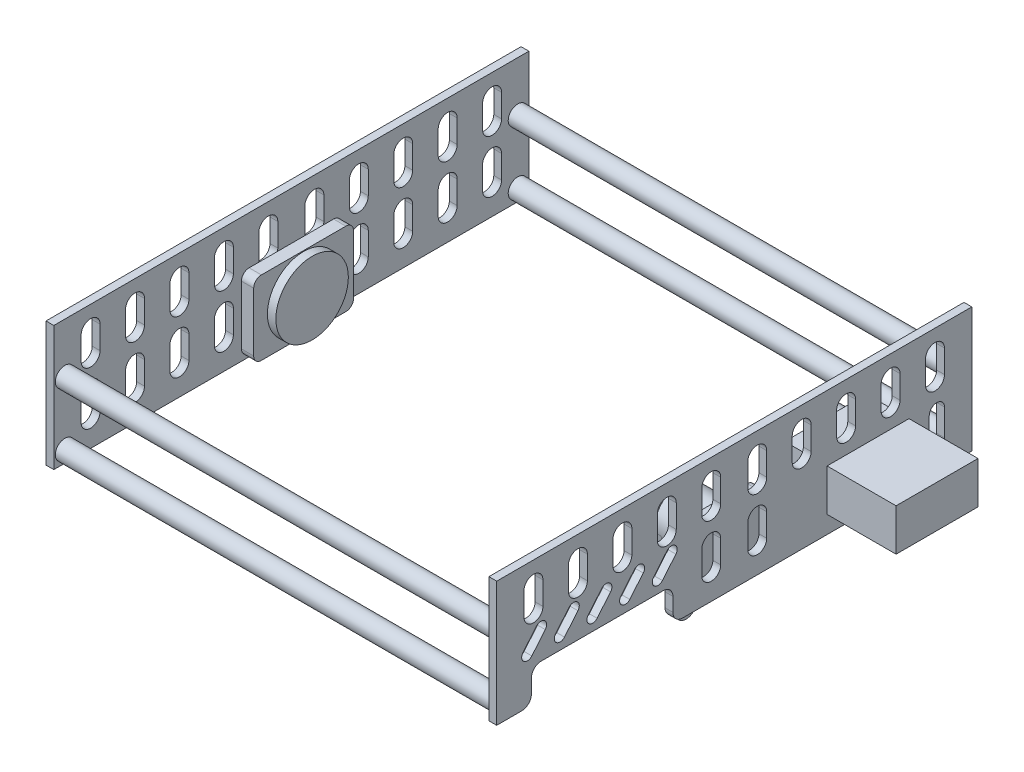
SolidWorks part; units mm, degrees
ref_plane "Front Plane" through (0, 0, 0) normal (0, 0, 1) x (1, 0, 0)
ref_plane "Top Plane" through (0, 0, 0) normal (0, 1, 0) x (1, 0, 0)
ref_plane "Right Plane" through (0, 0, 0) normal (1, 0, 0) x (0, 0, -1)
sketch "Sketch1" plane through (0, 0, 0) normal (1, 0, 0) x (0, 0, -1)
  line L0 (0, 0) -> (0, -16.4338) construction
  line L1 (0, 0) -> (55.8004, 0) construction
  line L2 (0, -16.4338) -> (117.9322, -16.4338) construction
  line L3 (117.9322, -16.4338) -> (117.9322, 0) construction
  line L4 (-2.5019, -18.9357) -> (120.4341, -18.9357) construction
  line L5 (-2.5019, 2.5019) -> (120.4341, 2.5019) construction
  line L6 (-2.5019, 2.5019) -> (-2.5019, -18.9357) construction
  line L7 (120.4341, 2.5019) -> (120.4341, -18.9357) construction
  circle A0 centre (0, 0) radius 2.5019
  circle A1 centre (0, -16.4338) radius 2.5019
  circle A2 centre (117.9322, -16.4338) radius 2.5019
  circle A3 centre (117.9322, 0) radius 2.5019
  dimension "D2" = 5.0038
  dimension "D3" = 21.4376
  dimension "D4" = 122.936
extrude "Boss-Extrude1" add sketch "Sketch1" along normal blind 115.316
ref_plane "Plane1" through (12.7, 0, 0) normal (1, 0, 0) x (0, 0, -1)
sketch "Sketch5" plane through (0, 0, 0) normal (1, 0, 0) x (0, 0, -1)
  line L4 (0, 0) -> (117.9322, -16.4338) construction
  line L5 (58.9661, 12.954) -> (58.9661, -19.558) construction
  line L6 (4.2291, -14.9987) -> (4.2291, 9.7028) construction
  line L8 (6.6941, 1.2458) -> (6.6941, 7.2378) construction
  line L10 (4.2291, 9.7028) -> (113.7031, 9.7028) construction
  line L15 (113.7031, -14.9987) -> (4.2291, -14.9987) construction
  line L20 (117.9322, 0) -> (0, -16.4338) construction
  line L29 (64.9581, 1.2458) -> (64.9581, 7.2378) construction
  line L38 (67.4231, 1.2458) -> (67.4231, 7.2378)
  line L45 (62.4931, 1.2458) -> (62.4931, 7.2378)
  line L52 (64.9581, -12.5337) -> (64.9581, -6.5417) construction
  line L61 (67.4231, -12.5337) -> (67.4231, -6.5417)
  line L70 (62.4931, -12.5337) -> (62.4931, -6.5417)
  line L76 (-2.8829, -19.558) -> (120.8151, -19.558)
  line L77 (-2.8829, -19.558) -> (-2.8829, 12.954)
  line L78 (-2.8829, 12.954) -> (120.8151, 12.954)
  line L79 (120.8151, -19.558) -> (120.8151, 12.954)
  line L80 (76.5281, -12.5337) -> (76.5281, -6.5417) construction
  line L81 (78.9931, -12.5337) -> (78.9931, -6.5417)
  line L82 (4.2291, 1.2458) -> (4.2291, 7.2378)
  line L83 (9.1591, 1.2458) -> (9.1591, 7.2378)
  line L84 (4.2291, 9.7028) -> (9.1591, 9.7028) construction
  line L85 (9.1591, 9.7028) -> (9.1591, -1.2192) construction
  line L86 (9.1591, -1.2192) -> (4.2291, -1.2192) construction
  line L87 (4.2291, -1.2192) -> (4.2291, 9.7028) construction
  line L88 (18.2641, 1.2458) -> (18.2641, 7.2378) construction
  line L89 (15.7991, 1.2458) -> (15.7991, 7.2378)
  line L90 (20.7291, 1.2458) -> (20.7291, 7.2378)
  line L91 (29.8341, 1.2458) -> (29.8341, 7.2378) construction
  line L92 (27.3691, 1.2458) -> (27.3691, 7.2378)
  line L93 (32.2991, 1.2458) -> (32.2991, 7.2378)
  line L94 (41.4041, 1.2458) -> (41.4041, 7.2378) construction
  line L95 (38.9391, 1.2458) -> (38.9391, 7.2378)
  line L96 (43.8691, 1.2458) -> (43.8691, 7.2378)
  line L97 (52.9741, 1.2458) -> (52.9741, 7.2378) construction
  line L98 (50.5091, 1.2458) -> (50.5091, 7.2378)
  line L99 (55.4391, 1.2458) -> (55.4391, 7.2378)
  line L100 (18.2641, -12.5337) -> (18.2641, -6.5417) construction
  line L101 (15.7991, -12.5337) -> (15.7991, -6.5417)
  line L102 (20.7291, -12.5337) -> (20.7291, -6.5417)
  line L103 (29.8341, -12.5337) -> (29.8341, -6.5417) construction
  line L104 (27.3691, -12.5337) -> (27.3691, -6.5417)
  line L105 (32.2991, -12.5337) -> (32.2991, -6.5417)
  line L106 (41.4041, -12.5337) -> (41.4041, -6.5417) construction
  line L107 (38.9391, -12.5337) -> (38.9391, -6.5417)
  line L108 (43.8691, -12.5337) -> (43.8691, -6.5417)
  line L109 (52.9741, -12.5337) -> (52.9741, -6.5417) construction
  line L110 (50.5091, -12.5337) -> (50.5091, -6.5417)
  line L111 (55.4391, -12.5337) -> (55.4391, -6.5417)
  line L112 (6.6941, -12.5337) -> (6.6941, -6.5417) construction
  line L113 (4.2291, -12.5337) -> (4.2291, -6.5417)
  line L114 (9.1591, -12.5337) -> (9.1591, -6.5417)
  line L116 (74.0631, -12.5337) -> (74.0631, -6.5417)
  line L117 (113.7031, 9.7028) -> (113.7031, -14.9987) construction
  line L118 (76.5281, 1.2458) -> (76.5281, 7.2378) construction
  line L119 (78.9931, 1.2458) -> (78.9931, 7.2378)
  line L120 (74.0631, 1.2458) -> (74.0631, 7.2378)
  line L121 (88.0981, 1.2458) -> (88.0981, 7.2378) construction
  line L122 (90.5631, 1.2458) -> (90.5631, 7.2378)
  line L123 (85.6331, 1.2458) -> (85.6331, 7.2378)
  line L124 (88.0981, -12.5337) -> (88.0981, -6.5417) construction
  line L125 (90.5631, -12.5337) -> (90.5631, -6.5417)
  line L126 (85.6331, -12.5337) -> (85.6331, -6.5417)
  line L127 (99.6681, -12.5337) -> (99.6681, -6.5417) construction
  line L128 (102.1331, -12.5337) -> (102.1331, -6.5417)
  line L129 (97.2031, -12.5337) -> (97.2031, -6.5417)
  line L130 (99.6681, 1.2458) -> (99.6681, 7.2378) construction
  line L131 (102.1331, 1.2458) -> (102.1331, 7.2378)
  line L132 (97.2031, 1.2458) -> (97.2031, 7.2378)
  line L133 (111.2381, 1.2458) -> (111.2381, 7.2378) construction
  line L134 (113.7031, 1.2458) -> (113.7031, 7.2378)
  line L135 (108.7731, 1.2458) -> (108.7731, 7.2378)
  line L136 (111.2381, -12.5337) -> (111.2381, -6.5417) construction
  line L137 (113.7031, -12.5337) -> (113.7031, -6.5417)
  line L138 (108.7731, -12.5337) -> (108.7731, -6.5417)
  line L140 (-6.1459, 2.5019) -> (0, 2.5019) construction
  arc A40 (4.2291, 1.2458) -> (9.1591, 1.2458) centre (6.6941, 1.2458) ccw
  arc A41 (9.1591, 7.2378) -> (4.2291, 7.2378) centre (6.6941, 7.2378) ccw
  arc A42 (15.7991, 1.2458) -> (20.7291, 1.2458) centre (18.2641, 1.2458) ccw
  arc A43 (20.7291, 7.2378) -> (15.7991, 7.2378) centre (18.2641, 7.2378) ccw
  arc A44 (27.3691, 1.2458) -> (32.2991, 1.2458) centre (29.8341, 1.2458) ccw
  arc A45 (32.2991, 7.2378) -> (27.3691, 7.2378) centre (29.8341, 7.2378) ccw
  arc A46 (38.9391, 1.2458) -> (43.8691, 1.2458) centre (41.4041, 1.2458) ccw
  arc A47 (43.8691, 7.2378) -> (38.9391, 7.2378) centre (41.4041, 7.2378) ccw
  arc A48 (50.5091, 1.2458) -> (55.4391, 1.2458) centre (52.9741, 1.2458) ccw
  arc A49 (55.4391, 7.2378) -> (50.5091, 7.2378) centre (52.9741, 7.2378) ccw
  arc A50 (15.7991, -12.5337) -> (20.7291, -12.5337) centre (18.2641, -12.5337) ccw
  arc A51 (20.7291, -6.5417) -> (15.7991, -6.5417) centre (18.2641, -6.5417) ccw
  arc A52 (27.3691, -12.5337) -> (32.2991, -12.5337) centre (29.8341, -12.5337) ccw
  arc A53 (32.2991, -6.5417) -> (27.3691, -6.5417) centre (29.8341, -6.5417) ccw
  arc A54 (38.9391, -12.5337) -> (43.8691, -12.5337) centre (41.4041, -12.5337) ccw
  arc A55 (43.8691, -6.5417) -> (38.9391, -6.5417) centre (41.4041, -6.5417) ccw
  arc A56 (50.5091, -12.5337) -> (55.4391, -12.5337) centre (52.9741, -12.5337) ccw
  arc A57 (55.4391, -6.5417) -> (50.5091, -6.5417) centre (52.9741, -6.5417) ccw
  arc A58 (4.2291, -12.5337) -> (9.1591, -12.5337) centre (6.6941, -12.5337) ccw
  arc A59 (9.1591, -6.5417) -> (4.2291, -6.5417) centre (6.6941, -6.5417) ccw
  circle A60 centre (0, 0) radius 2.5019 construction
  circle A61 centre (0, -16.4338) radius 2.5019 construction
  circle A62 centre (117.9322, 0) radius 2.5019 construction
  circle A63 centre (117.9322, -16.4338) radius 2.5019 construction
  arc A64 (67.4231, 1.2458) -> (62.4931, 1.2458) centre (64.9581, 1.2458) cw
  arc A65 (62.4931, 7.2378) -> (67.4231, 7.2378) centre (64.9581, 7.2378) cw
  arc A66 (67.4231, -12.5337) -> (62.4931, -12.5337) centre (64.9581, -12.5337) cw
  arc A67 (62.4931, -6.5417) -> (67.4231, -6.5417) centre (64.9581, -6.5417) cw
  arc A68 (78.9931, -12.5337) -> (74.0631, -12.5337) centre (76.5281, -12.5337) cw
  arc A69 (74.0631, -6.5417) -> (78.9931, -6.5417) centre (76.5281, -6.5417) cw
  arc A70 (78.9931, 1.2458) -> (74.0631, 1.2458) centre (76.5281, 1.2458) cw
  arc A71 (74.0631, 7.2378) -> (78.9931, 7.2378) centre (76.5281, 7.2378) cw
  arc A72 (90.5631, 1.2458) -> (85.6331, 1.2458) centre (88.0981, 1.2458) cw
  arc A73 (85.6331, 7.2378) -> (90.5631, 7.2378) centre (88.0981, 7.2378) cw
  arc A74 (90.5631, -12.5337) -> (85.6331, -12.5337) centre (88.0981, -12.5337) cw
  arc A75 (85.6331, -6.5417) -> (90.5631, -6.5417) centre (88.0981, -6.5417) cw
  arc A76 (102.1331, -12.5337) -> (97.2031, -12.5337) centre (99.6681, -12.5337) cw
  arc A77 (97.2031, -6.5417) -> (102.1331, -6.5417) centre (99.6681, -6.5417) cw
  arc A78 (102.1331, 1.2458) -> (97.2031, 1.2458) centre (99.6681, 1.2458) cw
  arc A79 (97.2031, 7.2378) -> (102.1331, 7.2378) centre (99.6681, 7.2378) cw
  arc A80 (113.7031, 1.2458) -> (108.7731, 1.2458) centre (111.2381, 1.2458) cw
  arc A81 (108.7731, 7.2378) -> (113.7031, 7.2378) centre (111.2381, 7.2378) cw
  arc A82 (113.7031, -12.5337) -> (108.7731, -12.5337) centre (111.2381, -12.5337) cw
  arc A83 (108.7731, -6.5417) -> (113.7031, -6.5417) centre (111.2381, -6.5417) cw
  point P15 (58.9661, -8.2169)
  point P19 (64.9581, 4.2418)
  point P26 (64.9581, -9.5377)
  point P36 (76.5281, -9.5377)
  point P43 (76.5281, 4.2418)
  point P50 (88.0981, 4.2418)
  point P57 (88.0981, -9.5377)
  point P64 (99.6681, -9.5377)
  point P71 (99.6681, 4.2418)
  point P78 (111.2381, 4.2418)
  point P88 (111.2381, -9.5377)
  point P100 (58.9661, -7.9692)
  point P166 (6.6941, 4.2418)
  point P180 (18.2641, 4.2418)
  point P187 (29.8341, 4.2418)
  point P194 (41.4041, 4.2418)
  point P201 (52.9741, 4.2418)
  point P208 (18.2641, -9.5377)
  point P215 (29.8341, -9.5377)
  point P222 (41.4041, -9.5377)
  point P229 (52.9741, -9.5377)
  point P236 (6.6941, -9.5377)
  dimension "D3" = 123.698
  dimension "D2" = 16.5
  dimension "D4" = 10.4521
  dimension "D11" = 32.512
  dimension "D13" = 3.2512
  dimension "D14" = 7.112
  dimension "D15" = 4.93
  dimension "D16" = 10.922
  dimension "D19" = 13.7795
  dimension "D17" = 5
  dimension "D18" = 2
extrude "Boss-Extrude3" add sketch "Sketch5" along normal blind 2.032
ref_plane "Plane2" through (115.316, 0, 0) normal (1, 0, 0) x (0, 0, -1)
sketch "Sketch6" plane through (115.316, 0, 0) normal (1, 0, 0) x (0, 0, -1)
  line L0 (120.8151, 12.954) -> (-2.8829, 12.954) construction
  line L1 (-2.8829, -19.558) -> (3.6195, -19.558)
  line L2 (-2.8829, -19.558) -> (-2.8829, 12.954)
  line L3 (-2.8829, 12.954) -> (120.8151, 12.954)
  line L4 (120.8151, -19.558) -> (120.8151, 12.954)
  line L5 (-2.8829, -19.558) -> (120.8151, 12.954) construction
  line L6 (-2.8829, 12.954) -> (120.8151, -19.558) construction
  line L7 (-2.8829, 12.954) -> (-2.8829, -19.558) construction
  line L8 (6.1595, -17.018) -> (6.1595, -13.4112)
  line L9 (8.6995, -10.8712) -> (40.4495, -10.8712)
  line L10 (42.9895, -13.4112) -> (42.9895, -17.018)
  line L11 (45.5295, -19.558) -> (120.8151, -19.558)
  line L12 (52.9741, -6.5417) -> (52.9741, -12.5337) construction
  line L13 (55.4391, -6.5417) -> (55.4391, -12.5337)
  line L14 (50.5091, -6.5417) -> (50.5091, -12.5337)
  line L15 (64.9581, -6.5417) -> (64.9581, -12.5337) construction
  line L16 (67.4231, -6.5417) -> (67.4231, -12.5337)
  line L17 (62.4931, -6.5417) -> (62.4931, -12.5337)
  line L18 (111.7192, -6.0606) -> (111.7192, -13.0148) construction
  line L19 (113.7031, -6.0606) -> (113.7031, -13.0148)
  line L20 (109.7354, -6.0606) -> (109.7354, -13.0148)
  line L21 (113.7031, -4.0767) -> (50.5091, -4.0767) construction
  line L22 (50.5091, -4.0767) -> (50.5091, -14.9987) construction
  line L23 (50.5091, -14.9987) -> (113.7031, -14.9987) construction
  line L24 (113.7031, -14.9987) -> (113.7031, -4.0767) construction
  line L25 (113.7031, -12.5337) -> (113.7031, -6.5417) construction
  line L27 (104.4658, -4.0767) -> (83.1362, -4.0767)
  line L28 (104.4658, -4.0767) -> (104.4658, -14.9987)
  line L29 (104.4658, -14.9987) -> (83.1362, -14.9987)
  line L30 (83.1362, -4.0767) -> (83.1362, -14.9987)
  line L31 (104.4658, -4.0767) -> (83.1362, -14.9987) construction
  line L32 (104.4658, -14.9987) -> (83.1362, -4.0767) construction
  line L88 (15.7991, 7.2378) -> (15.7991, 1.2458)
  line L89 (20.7291, 1.2458) -> (20.7291, 7.2378)
  line L90 (9.1591, 1.2458) -> (9.1591, 7.2378)
  line L91 (4.2291, 7.2378) -> (4.2291, 1.2458)
  line L92 (9.1591, 1.2458) -> (9.1591, 7.2378)
  line L93 (4.2291, 7.2378) -> (4.2291, 1.2458)
  line L94 (27.3691, 7.2378) -> (27.3691, 1.2458)
  line L95 (32.2991, 1.2458) -> (32.2991, 7.2378)
  line L96 (38.9391, 7.2378) -> (38.9391, 1.2458)
  line L97 (43.8691, 1.2458) -> (43.8691, 7.2378)
  line L98 (50.5091, 7.2378) -> (50.5091, 1.2458)
  line L99 (55.4391, 1.2458) -> (55.4391, 7.2378)
  line L100 (15.7991, 7.2378) -> (15.7991, 1.2458) construction
  line L101 (58.9661, 12.954) -> (58.9661, -19.558) construction
  line L102 (62.4931, 1.2458) -> (62.4931, 7.2378)
  line L103 (67.4231, 7.2378) -> (67.4231, 1.2458)
  line L104 (74.0631, 1.2458) -> (74.0631, 7.2378)
  line L105 (78.9931, 7.2378) -> (78.9931, 1.2458)
  line L106 (85.6331, 1.2458) -> (85.6331, 7.2378)
  line L107 (90.5631, 7.2378) -> (90.5631, 1.2458)
  line L108 (97.2031, 1.2458) -> (97.2031, 7.2378)
  line L109 (102.1331, 7.2378) -> (102.1331, 1.2458)
  line L110 (113.7031, 7.2378) -> (113.7031, 1.2458)
  line L111 (108.7731, 1.2458) -> (108.7731, 7.2378)
  arc A0 (55.4391, -6.5417) -> (50.5091, -6.5417) centre (52.9741, -6.5417) ccw
  arc A1 (50.5091, -12.5337) -> (55.4391, -12.5337) centre (52.9741, -12.5337) ccw
  arc A4 (67.4231, -6.5417) -> (62.4931, -6.5417) centre (64.9581, -6.5417) ccw
  arc A6 (62.4931, -12.5337) -> (67.4231, -12.5337) centre (64.9581, -12.5337) ccw
  arc A10 (55.4391, -6.5417) -> (50.5091, -6.5417) centre (52.9741, -6.5417) ccw construction
  arc A11 (50.5091, -12.5337) -> (55.4391, -12.5337) centre (52.9741, -12.5337) ccw construction
  arc A12 (67.4231, -6.5417) -> (62.4931, -6.5417) centre (64.9581, -6.5417) ccw construction
  arc A13 (62.4931, -12.5337) -> (67.4231, -12.5337) centre (64.9581, -12.5337) ccw construction
  arc A14 (113.7031, -6.0606) -> (109.7354, -6.0606) centre (111.7192, -6.0606) ccw
  arc A15 (109.7354, -13.0148) -> (113.7031, -13.0148) centre (111.7192, -13.0148) ccw
  arc A70 (20.7291, 7.2378) -> (15.7991, 7.2378) centre (18.2641, 7.2378) ccw
  arc A71 (15.7991, 1.2458) -> (20.7291, 1.2458) centre (18.2641, 1.2458) ccw
  arc A72 (4.2291, 1.2458) -> (9.1591, 1.2458) centre (6.6941, 1.2458) ccw
  arc A73 (9.1591, 7.2378) -> (4.2291, 7.2378) centre (6.6941, 7.2378) ccw
  arc A74 (4.2291, 1.2458) -> (9.1591, 1.2458) centre (6.6941, 1.2458) ccw
  arc A75 (9.1591, 7.2378) -> (4.2291, 7.2378) centre (6.6941, 7.2378) ccw
  arc A76 (32.2991, 7.2378) -> (27.3691, 7.2378) centre (29.8341, 7.2378) ccw
  arc A77 (27.3691, 1.2458) -> (32.2991, 1.2458) centre (29.8341, 1.2458) ccw
  arc A78 (43.8691, 7.2378) -> (38.9391, 7.2378) centre (41.4041, 7.2378) ccw
  arc A79 (38.9391, 1.2458) -> (43.8691, 1.2458) centre (41.4041, 1.2458) ccw
  arc A80 (55.4391, 7.2378) -> (50.5091, 7.2378) centre (52.9741, 7.2378) ccw
  arc A81 (50.5091, 1.2458) -> (55.4391, 1.2458) centre (52.9741, 1.2458) ccw
  arc A82 (62.4931, 7.2378) -> (67.4231, 7.2378) centre (64.9581, 7.2378) cw
  arc A83 (67.4231, 1.2458) -> (62.4931, 1.2458) centre (64.9581, 1.2458) cw
  arc A84 (74.0631, 7.2378) -> (78.9931, 7.2378) centre (76.5281, 7.2378) cw
  arc A85 (78.9931, 1.2458) -> (74.0631, 1.2458) centre (76.5281, 1.2458) cw
  arc A86 (85.6331, 7.2378) -> (90.5631, 7.2378) centre (88.0981, 7.2378) cw
  arc A87 (90.5631, 1.2458) -> (85.6331, 1.2458) centre (88.0981, 1.2458) cw
  arc A88 (97.2031, 7.2378) -> (102.1331, 7.2378) centre (99.6681, 7.2378) cw
  arc A89 (102.1331, 1.2458) -> (97.2031, 1.2458) centre (99.6681, 1.2458) cw
  arc A90 (108.7731, 7.2378) -> (113.7031, 7.2378) centre (111.2381, 7.2378) cw
  arc A91 (113.7031, 1.2458) -> (108.7731, 1.2458) centre (111.2381, 1.2458) cw
  arc A92 (42.9895, -17.018) -> (45.5295, -19.558) centre (45.5295, -17.018) ccw
  arc A93 (40.4495, -10.8712) -> (42.9895, -13.4112) centre (40.4495, -13.4112) cw
  arc A94 (6.1595, -13.4112) -> (8.6995, -10.8712) centre (8.6995, -13.4112) cw
  arc A95 (6.1595, -17.018) -> (3.6195, -19.558) centre (3.6195, -17.018) cw
  point P0 (58.9661, -3.302)
  point P79 (42.9895, -19.558)
  point P82 (42.9895, -10.8712)
  point P85 (6.1595, -10.8712)
  point P88 (6.1595, -19.558)
  point P91 (52.9741, -9.5377)
  point P96 (64.9581, -9.5377)
  point P117 (111.7192, -9.5377)
  point P128 (93.801, -9.5377)
  dimension "D6" = 2.54
  dimension "D3" = 8.6868
  dimension "D4" = 36.83
  dimension "D5" = 9.0424
  dimension "D1" = 0
  dimension "D2" = 5
extrude "Boss-Extrude4" add sketch "Sketch6" along normal blind 2.032 separate body
sketch "Sketch7" plane through (117.348, 0, 0) normal (1, 0, 0) x (0, 0, -1)
  line L0 (5.1171, -7.5212) -> (8.6171, -3.326) construction
  line L1 (3.9653, -6.5603) -> (7.4653, -2.3651)
  line L2 (6.2689, -8.4821) -> (9.7689, -4.2869)
  line L3 (13.6171, -7.5212) -> (17.1171, -3.326) construction
  line L4 (12.4653, -6.5603) -> (15.9653, -2.3651)
  line L5 (14.7689, -8.4821) -> (18.2689, -4.2869)
  line L6 (22.1171, -7.5212) -> (25.6171, -3.326) construction
  line L7 (20.9653, -6.5603) -> (24.4653, -2.3651)
  line L8 (23.2689, -8.4821) -> (26.7689, -4.2869)
  line L9 (30.6171, -7.5212) -> (34.1171, -3.326) construction
  line L10 (29.4653, -6.5603) -> (32.9653, -2.3651)
  line L11 (31.7689, -8.4821) -> (35.2689, -4.2869)
  line L12 (39.1171, -7.5212) -> (42.6171, -3.326) construction
  line L13 (37.9653, -6.5603) -> (41.4653, -2.3651)
  line L14 (40.2689, -8.4821) -> (43.7689, -4.2869)
  line L15 (44.1171, -9.0212) -> (3.6171, -9.0212) construction
  line L16 (8.6995, -10.8712) -> (40.4495, -10.8712) construction
  line L17 (3.6171, -9.0212) -> (3.6171, -1.826) construction
  line L18 (-2.8829, 12.954) -> (-2.8829, -19.558) construction
  line L19 (3.6171, -1.826) -> (44.1171, -1.826) construction
  line L20 (44.1171, -1.826) -> (44.1171, -9.0212) construction
  line L21 (120.8151, 12.954) -> (-2.8829, 12.954) construction
  line L22 (10.1171, -1.826) -> (10.1171, -9.0212) construction
  arc A0 (3.9653, -6.5603) -> (6.2689, -8.4821) centre (5.1171, -7.5212) ccw
  arc A1 (9.7689, -4.2869) -> (7.4653, -2.3651) centre (8.6171, -3.326) ccw
  arc A2 (12.4653, -6.5603) -> (14.7689, -8.4821) centre (13.6171, -7.5212) ccw
  arc A3 (18.2689, -4.2869) -> (15.9653, -2.3651) centre (17.1171, -3.326) ccw
  arc A4 (20.9653, -6.5603) -> (23.2689, -8.4821) centre (22.1171, -7.5212) ccw
  arc A5 (26.7689, -4.2869) -> (24.4653, -2.3651) centre (25.6171, -3.326) ccw
  arc A6 (29.4653, -6.5603) -> (31.7689, -8.4821) centre (30.6171, -7.5212) ccw
  arc A7 (35.2689, -4.2869) -> (32.9653, -2.3651) centre (34.1171, -3.326) ccw
  arc A8 (37.9653, -6.5603) -> (40.2689, -8.4821) centre (39.1171, -7.5212) ccw
  arc A9 (43.7689, -4.2869) -> (41.4653, -2.3651) centre (42.6171, -3.326) ccw
  point P2 (6.8671, -5.4236)
  point P10 (15.3671, -5.4236)
  point P17 (23.8671, -5.4236)
  point P24 (32.3671, -5.4236)
  point P31 (40.8671, -5.4236)
  dimension "D2" = 3
  dimension "D3" = 1.85
  dimension "D4" = 6.5
  dimension "D5" = 14.78
  dimension "D6" = 40.5
  dimension "D7" = 6.5
  dimension "D1" = 5
extrude "Cut-Extrude1" cut sketch "Sketch7" against normal up to surface (2.032 mm away) up to face at (115.316, -11.2437, -36.0384)
sketch "Sketch8" plane through (115.316, 0, 0) normal (-1, 0, 0) x (0, 0, 1)
  line L0 (-67.4231, -9.5377) -> (-50.5091, -9.5377) construction
  line L1 (-67.3513, -16.3825) -> (-50.5809, -16.3825)
  line L2 (-69.3513, -14.3825) -> (-69.3513, -4.6929)
  line L3 (-67.3513, -2.6929) -> (-50.5809, -2.6929)
  line L4 (-48.5809, -14.3825) -> (-48.5809, -4.6929)
  line L5 (-69.3513, -16.3825) -> (-48.5809, -2.6929) construction
  line L6 (-69.3513, -2.6929) -> (-48.5809, -16.3825) construction
  line L7 (-67.4231, -12.5337) -> (-67.4231, -6.5417) construction
  line L8 (-50.5091, -6.5417) -> (-50.5091, -12.5337) construction
  arc A0 (-67.3513, -16.3825) -> (-69.3513, -14.3825) centre (-67.3513, -14.3825) cw
  arc A1 (-50.5809, -16.3825) -> (-48.5809, -14.3825) centre (-50.5809, -14.3825) ccw
  arc A2 (-50.5809, -2.6929) -> (-48.5809, -4.6929) centre (-50.5809, -4.6929) cw
  arc A3 (-69.3513, -4.6929) -> (-67.3513, -2.6929) centre (-67.3513, -4.6929) cw
  point P0 (-58.9661, -9.5377)
  dimension "D1" = 2
extrude "Boss-Extrude5" add sketch "Sketch8" along normal blind 3
sketch "Sketch9" plane through (112.316, 0, 0) normal (-1, 0, 0) x (0, 0, 1)
  line L0 (-58.9661, -2.6929) -> (-58.9661, -16.3825) construction
  line L1 (-50.5809, -2.6929) -> (-67.3513, -2.6929) construction
  line L2 (-67.3513, -16.3825) -> (-50.5809, -16.3825) construction
  line L4 (-58.9661, -2.8929) -> (-68.2231, -2.8929) construction
  line L6 (-50.5809, -2.6929) -> (-67.3513, -2.6929) construction
  circle A0 centre (-58.9661, -9.5377) radius 6.6448
  arc A3 (-67.3513, -2.6929) -> (-69.3513, -4.6929) centre (-67.3513, -4.6929) ccw construction
  dimension "D1" = 0.2
extrude "Boss-Extrude6" add sketch "Sketch9" along normal blind 9
sketch "Sketch10" plane through (103.316, 0, 0) normal (-1, 0, 0) x (0, 0, 1)
  line L2 (-58.9661, -22.1504) -> (-58.9661, -9.5377) construction
  line L3 (-65.4876, -10.8118) -> (-61.616, -30.6295)
  line L5 (-65.4876, -10.8118) -> (-52.4446, -10.8118)
  line L6 (-56.3162, -30.6295) -> (-52.4446, -10.8118)
  line L7 (-61.616, -30.6295) -> (-56.3162, -30.6295) construction
  line L8 (-58.9661, -32.8118) -> (-55.7901, -32.8118) construction
  circle A0 centre (-58.9661, -9.5377) radius 6.6448 construction
  circle A3 centre (-58.9661, -9.5377) radius 6.6448 construction
  arc A4 (-61.616, -30.6295) -> (-56.3162, -30.6295) centre (-58.9661, -30.1118) ccw
  dimension "D2" = 2.7
  dimension "D1" = 22
extrude "Boss-Extrude7" add sketch "Sketch10" against normal blind 1.5
ref_plane "Plane3" through (115.316, -4.0767, -104.4658) normal (0, 0, 1) x (1, 0, 0)
sketch "Sketch12" plane through (0, -4.0767, 0) normal (0, -1, 0) x (1, 0, 0)
  line L0 (115.316, -83.1362) -> (115.316, -80.8362)
  line L1 (115.316, -80.8362) -> (113.616, -80.8362)
  line L2 (113.616, -80.8362) -> (113.616, -83.1362)
  line L3 (113.616, -83.1362) -> (106.316, -83.1362)
  line L4 (106.316, -83.1362) -> (106.316, -104.4658)
  line L11 (135.316, -104.4658) -> (135.316, -83.1362)
  line L12 (135.316, -83.1362) -> (115.316, -83.1362)
  line L13 (115.316, -93.801) -> (106.316, -93.801) construction
  line L14 (115.316, -104.4658) -> (115.316, -83.1362) construction
  line L15 (135.316, -104.4658) -> (115.316, -104.4658)
  line L16 (115.316, -104.4658) -> (115.316, -106.7658)
  line L17 (115.316, -106.7658) -> (113.616, -106.7658)
  line L18 (113.616, -106.7658) -> (113.616, -104.4658)
  line L19 (113.616, -104.4658) -> (106.316, -104.4658)
  point P8 (111.6241, -80.9739)
  point P11 (0, 0)
  point P12 (0, 0)
  point P13 (0, 0)
  point P17 (135.316, -93.801)
  dimension "D1" = 1.7
  dimension "D2" = 9
  dimension "D3" = 2.3
  dimension "D4" = 20
extrude "Boss-Extrude8" add sketch "Sketch12" along normal up to surface (10.922 mm away) up to face at (116.332, -14.9987, -93.801)
sketch "Sketch13" plane through (106.316, 0, 0) normal (-1, 0, 0) x (0, 0, 1)
  line L0 (-104.4658, -9.5377) -> (-83.1362, -9.5377) construction
  line L1 (-104.4658, -14.9987) -> (-104.4658, -4.0767) construction
  line L2 (-83.1362, -14.9987) -> (-83.1362, -4.0767) construction
  line L3 (-103.7658, -9.5377) -> (-103.7658, -4.0767) construction
  line L4 (-83.1362, -4.0767) -> (-104.4658, -4.0767) construction
  circle A0 centre (-99.7658, -9.5377) radius 4
  dimension "D1" = 8
  dimension "D2" = 0.7
extrude "Boss-Extrude9" add sketch "Sketch13" along normal blind 0.7
sketch "Sketch15" plane through (105.616, 0, 0) normal (-1, 0, 0) x (0, 0, 1)
  circle A0 centre (-99.7658, -9.5377) radius 3.25
  circle A1 centre (-99.7658, -9.5377) radius 4 construction
  dimension "D1" = 6.5
extrude "Boss-Extrude10" add sketch "Sketch15" along normal blind 3.7
sketch "Sketch14" plane through (101.916, 0, 0) normal (-1, 0, 0) x (0, 0, 1)
  line L0 (-58.9661, -32.8118) -> (-97.4687, -32.8118) construction
  line L1 (-97.4687, -32.8118) -> (-97.4687, -28.6269) construction
  line L2 (-99.7658, -30.8118) -> (-99.7658, -28.5118) construction
  line L3 (-99.7658, -9.5377) -> (-99.7658, -6.2877) construction
  line L4 (-99.7658, -6.2877) -> (-80.8362, -6.2877) construction
  line L5 (-99.7658, -30.8118) -> (-97.4687, -30.8118) construction
  line L6 (-99.7658, -9.5377) -> (-99.7658, -28.5118) construction
  line L7 (-102.0629, -28.6269) -> (-103.0117, -9.7004)
  line L8 (-96.5199, -9.7004) -> (-97.4687, -28.6269)
  line L9 (-80.8362, -14.9987) -> (-80.8362, -4.0767) construction
  arc A2 (-97.4687, -28.6269) -> (-102.0629, -28.6269) centre (-99.7658, -28.5118) cw
  arc A4 (-103.0117, -9.7004) -> (-96.5199, -9.7004) centre (-99.7658, -9.5377) cw
  arc A5 (-61.616, -30.6295) -> (-56.3162, -30.6295) centre (-58.9661, -30.1118) ccw construction
  circle A7 centre (-99.7658, -9.5377) radius 3.25 construction
  point P6 (-81.3862, -6.2877)
  dimension "D2" = 4.6
  dimension "D3" = 2
extrude "Boss-Extrude11" add sketch "Sketch14" along normal blind 1.2 contours L7 A4 L8 A2
sketch "Sketch16" plane through (2.032, 0, 0) normal (1, 0, 0) x (0, 0, -1)
  line L0 (55.4391, -12.5337) -> (62.4931, -12.5337) construction
  line L1 (47.9661, -18.758) -> (69.9661, -18.758)
  line L2 (45.9661, -16.758) -> (45.9661, -1.4767)
  line L3 (47.9661, 0.5233) -> (69.9661, 0.5233)
  line L4 (71.9661, -16.758) -> (71.9661, -1.4767)
  line L5 (45.9661, -18.758) -> (71.9661, 0.5233) construction
  line L6 (45.9661, 0.5233) -> (71.9661, -18.758) construction
  line L9 (62.4931, -12.5337) -> (58.9661, -12.5337) construction
  line L10 (58.9661, -12.5337) -> (58.9661, 0.5233) construction
  line L11 (-2.8829, -19.558) -> (120.8151, -19.558) construction
  line L12 (52.9741, -4.0767) -> (64.9581, -4.0767) construction
  arc A0 (69.9661, 0.5233) -> (71.9661, -1.4767) centre (69.9661, -1.4767) cw
  arc A1 (69.9661, -18.758) -> (71.9661, -16.758) centre (69.9661, -16.758) ccw
  arc A2 (47.9661, -18.758) -> (45.9661, -16.758) centre (47.9661, -16.758) cw
  arc A3 (45.9661, -1.4767) -> (47.9661, 0.5233) centre (47.9661, -1.4767) cw
  arc A4 (55.4391, -6.5417) -> (50.5091, -6.5417) centre (52.9741, -6.5417) ccw construction
  arc A5 (67.4231, -6.5417) -> (62.4931, -6.5417) centre (64.9581, -6.5417) ccw construction
  point P0 (58.9661, -9.1174)
  point P19 (45.9661, -18.758)
  dimension "D1" = 2
  dimension "D2" = 0.8
  dimension "D3" = 4.6
  dimension "D4" = 26
extrude "Boss-Extrude12" add sketch "Sketch16" along normal blind 3.2
sketch "Sketch17" plane through (5.232, 0, 0) normal (1, 0, 0) x (0, 0, -1)
  line L0 (45.9661, -9.1173) -> (71.9661, -9.1173) construction
  line L1 (45.9661, -1.4767) -> (45.9661, -16.758) construction
  line L2 (71.9661, -16.758) -> (71.9661, -1.4767) construction
  line L3 (58.9661, 0.3233) -> (70.8379, 0.3233) construction
  line L4 (69.9661, 0.5233) -> (47.9661, 0.5233) construction
  circle A0 centre (58.9661, -9.1174) radius 9.4407
  arc A1 (71.9661, -1.4767) -> (69.9661, 0.5233) centre (69.9661, -1.4767) ccw construction
  point P13 (58.9661, -0.9231)
  dimension "D1" = 0.2
extrude "Boss-Extrude13" add sketch "Sketch17" along normal blind 2.2
equation "\"x\"= 5cm"
